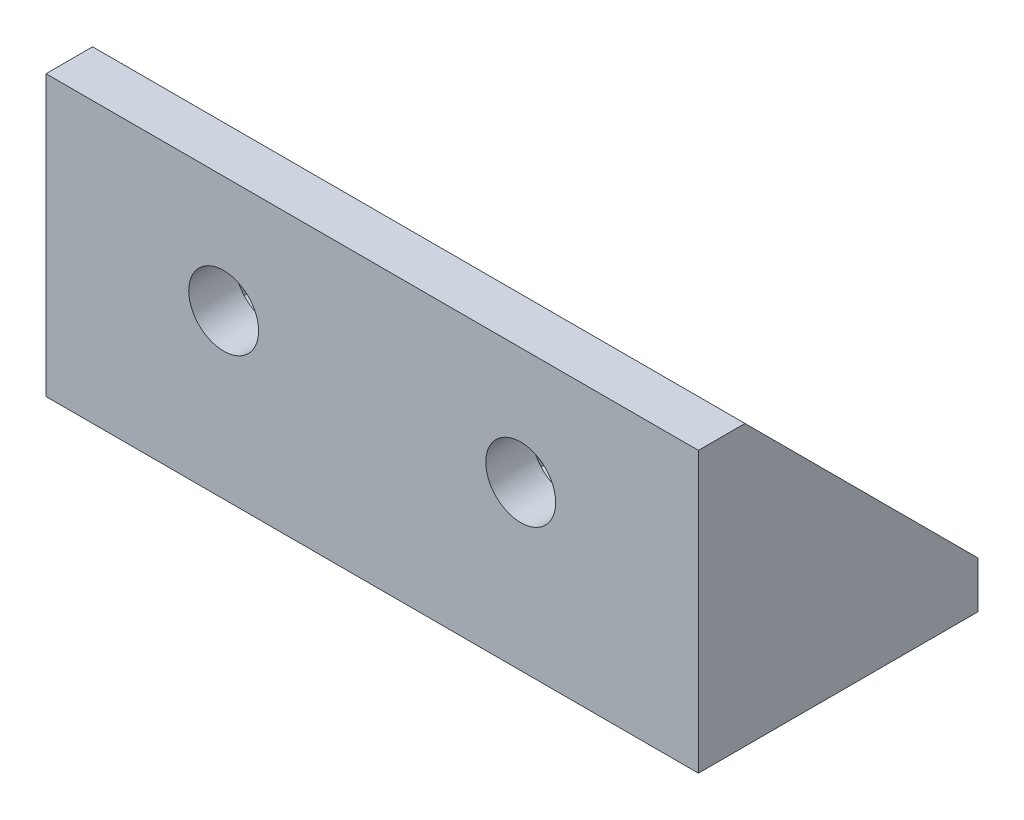
SolidWorks part; units mm, degrees
ref_plane "Alzado" through (0, 0, 0) normal (0, 0, 1) x (1, 0, 0)
ref_plane "Planta" through (0, 0, 0) normal (0, 1, 0) x (1, 0, 0)
ref_plane "Vista lateral" through (0, 0, 0) normal (1, 0, 0) x (0, 0, -1)
sketch "Croquis1" plane through (0, 0, 0) normal (0, 1, 0) x (1, 0, 0)
  line L0 (0, 10) -> (25, 10) construction
  line L1 (0, 0) -> (50, 0) construction
  line L2 (0, 0) -> (0, 20)
  line L3 (0, 20) -> (50, 20)
  line L4 (50, 0) -> (50, 20)
  line L5 (25, 10) -> (50, 10) construction
  line L6 (25, 10) -> (25, 20) construction
  line L8 (0, 0) -> (50, 0) construction
  line L9 (0, 0) -> (0, -4)
  line L10 (0, -4) -> (50, -4)
  line L11 (50, 0) -> (50, -4)
  circle A0 centre (12.5, 10) radius 2.5
  circle A1 centre (37.5, 10) radius 2.5
  dimension "D3" = 5
  dimension "D1" = 50
  dimension "D2" = 20
  dimension "D4" = 4
extrude "Saliente-Extruir1" add sketch "Croquis1" along normal blind 4
sketch "Croquis2" plane through (0, 4, 0) normal (0, 1, 0) x (1, 0, 0)
  line L0 (50, -4) -> (50, 20) construction
  line L1 (0, -4) -> (50, -4)
  line L2 (0, -4) -> (0, 0)
  line L3 (0, 0) -> (50, 0)
  line L4 (50, -4) -> (50, 0)
extrude "Saliente-Extruir2" add sketch "Croquis2" along normal blind 20
sketch "Croquis3" plane through (0, 0, 0) normal (-1, 0, 0) x (0, 0, 1)
  line L0 (-20, 4) -> (-20, 0) construction
  line L1 (0, 24) -> (4, 24) construction
  line L2 (4, 24) -> (4, 0) construction
  line L3 (-20, 0) -> (4, 0) construction
  line L4 (-20, 4) -> (-20, 0)
  line L5 (0, 24) -> (4, 24)
  line L6 (4, 24) -> (4, 0)
  line L7 (-20, 0) -> (4, 0)
  line L8 (-20, 4) -> (0, 24)
extrude "Saliente-Extruir3" add sketch "Croquis3" along normal blind 3 and the other way blind 53
sketch "Croquis4" plane through (0, 0, -20) normal (0, 0, -1) x (-1, 0, 0)
  line L0 (-25, 0) -> (-25, 24) construction
  line L1 (-53, 0) -> (3, 0) construction
  line L2 (-53, 24) -> (3, 24) construction
  line L3 (-48, 24) -> (-48, 4)
  line L4 (-53, 4) -> (3, 4) construction
  line L5 (-2, 4) -> (-2, 24)
  line L6 (-2, 14) -> (3, 14) construction
  line L7 (3, 24) -> (3, 4) construction
  line L8 (-48, 14) -> (-53, 14) construction
  line L9 (-53, 24) -> (-53, 4) construction
  line L10 (-27.5, 4) -> (-27.5, 24)
  line L11 (-22.5, 24) -> (-22.5, 4)
  line L12 (-27.5, 14) -> (-25, 14) construction
  line L13 (-25, 14) -> (-22.5, 14) construction
  line L14 (-39, 24) -> (-39, 4) construction
  line L15 (-45, 4) -> (-33, 4) construction
  line L16 (-45, 4) -> (-45, 24) construction
  line L17 (-45, 24) -> (-33, 24) construction
  line L18 (-33, 4) -> (-33, 24) construction
  line L19 (-53, 14) -> (-39, 14) construction
  line L20 (-39, 14) -> (-25, 14) construction
  line L21 (-48, 24) -> (-27.5, 24)
  line L22 (-48, 4) -> (-27.5, 4)
  line L23 (-22.5, 24) -> (-2, 24)
  line L24 (-22.5, 4) -> (-2, 4)
  dimension "D1" = 5
  dimension "D2" = 12
  dimension "D3" = 5
extrude "Cortar-Extruir1" cut sketch "Croquis4" against normal up to vertex (20 mm away)
sketch "Croquis5" plane through (0, 0, 0) normal (0, 0, -1) x (-1, 0, 0)
  line L0 (-48, 24) -> (-27.5, 4) construction
  line L1 (-25, 24) -> (-25, 4) construction
  line L2 (-27.5, 24) -> (-22.5, 24) construction
  line L3 (-27.5, 4) -> (-22.5, 4) construction
  circle A0 centre (-37.75, 14) radius 3
  circle A1 centre (-12.25, 14) radius 3
  dimension "D1" = 6
extrude "Cortar-Extruir2" cut sketch "Croquis5" against normal blind 17
sketch "Croquis6" plane through (0, 4, 0) normal (0, 1, 0) x (1, 0, 0)
  line L0 (2, 20) -> (22.5, 0) construction
  line L1 (25, 0) -> (25, 20) construction
  line L2 (27.5, 0) -> (22.5, 0) construction
  line L3 (27.5, 20) -> (22.5, 20) construction
  circle A0 centre (12.25, 10) radius 3
  circle A1 centre (37.75, 10) radius 3
  dimension "D1" = 6
extrude "Cortar-Extruir3" cut sketch "Croquis6" against normal blind 20
